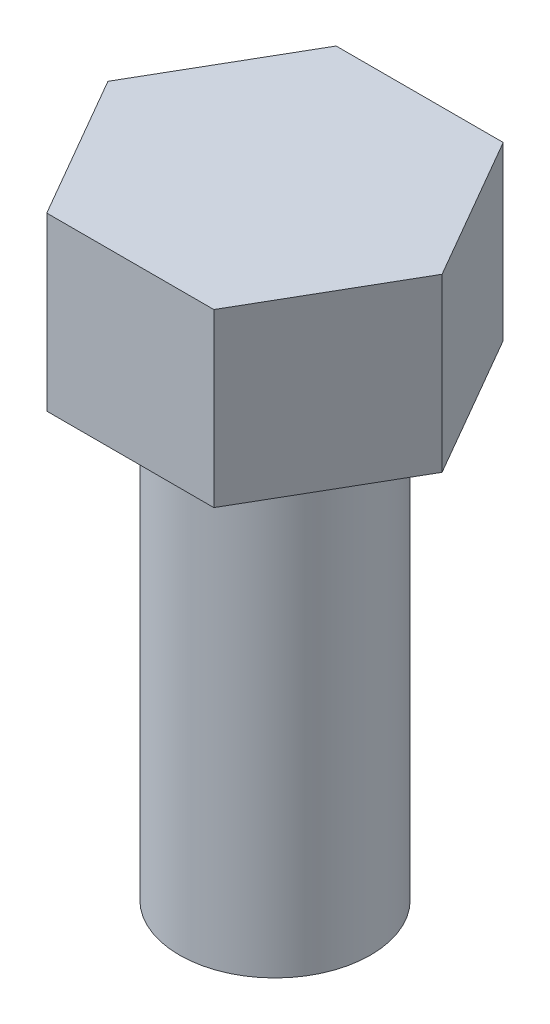
SolidWorks part; units mm, degrees
ref_plane "Front Plane" through (0, 0, 0) normal (0, 0, 1) x (1, 0, 0)
ref_plane "Top Plane" through (0, 0, 0) normal (0, 1, 0) x (1, 0, 0)
ref_plane "Right Plane" through (0, 0, 0) normal (1, 0, 0) x (0, 0, -1)
sketch "Sketch1" plane through (0, 0, 0) normal (0, 1, 0) x (1, 0, 0)
  line L0 (-2.3375, -4.0487) -> (2.3375, -4.0487)
  line L1 (2.3375, -4.0487) -> (4.675, 0)
  line L2 (4.675, 0) -> (2.3375, 4.0487)
  line L3 (2.3375, 4.0487) -> (-2.3375, 4.0487)
  line L4 (-2.3375, 4.0487) -> (-4.675, 0)
  line L5 (-4.675, 0) -> (-2.3375, -4.0487)
  circle A0 centre (0, 0) radius 2.675
sketch "Sketch2" plane through (0, 0, 0) normal (0, 1, 0) x (1, 0, 0)
  line L0 (-2.3375, 4.0487) -> (-4.675, 0) construction
  line L1 (-4.675, 0) -> (-2.3375, -4.0487) construction
  line L2 (-2.3375, -4.0487) -> (2.3375, -4.0487) construction
  line L3 (2.3375, -4.0487) -> (4.675, 0) construction
  line L4 (4.675, 0) -> (2.3375, 4.0487) construction
  line L5 (2.3375, 4.0487) -> (-2.3375, 4.0487) construction
  line L6 (-2.3375, 4.0487) -> (-4.675, 0)
  line L7 (-4.675, 0) -> (-2.3375, -4.0487)
  line L8 (-2.3375, -4.0487) -> (2.3375, -4.0487)
  line L9 (2.3375, -4.0487) -> (4.675, 0)
  line L10 (4.675, 0) -> (2.3375, 4.0487)
  line L11 (2.3375, 4.0487) -> (-2.3375, 4.0487)
extrude "Boss-Extrude1" add sketch "Sketch2" along normal blind 4.8
sketch "Sketch3" plane through (0, 0, 0) normal (0, -1, 0) x (1, 0, 0)
  circle A0 centre (0, 0) radius 2.675 construction
  circle A1 centre (0, 0) radius 2.675
extrude "Boss-Extrude2" add sketch "Sketch3" along normal blind 28.7
fillet "Fillet1" radius 0.25 1 edges at (0, 0, -2.675)
sketch "Sketch4" plane through (0, 0, 0) normal (0, 0, 1) x (1, 0, 0)
  line L0 (-2.3375, 4.8) -> (2.3375, 4.8) construction
  line L1 (-7.1485, -31.8736) -> (8.146, -31.8736)
  line L2 (-7.1485, -31.8736) -> (-7.1485, -12.7)
  line L3 (-7.1485, -12.7) -> (8.146, -12.7)
  line L4 (8.146, -31.8736) -> (8.146, -12.7)
  dimension "D1" = 17.5
extrude "Cut-Extrude1" cut sketch "Sketch4" against normal through all both and the other way through all
